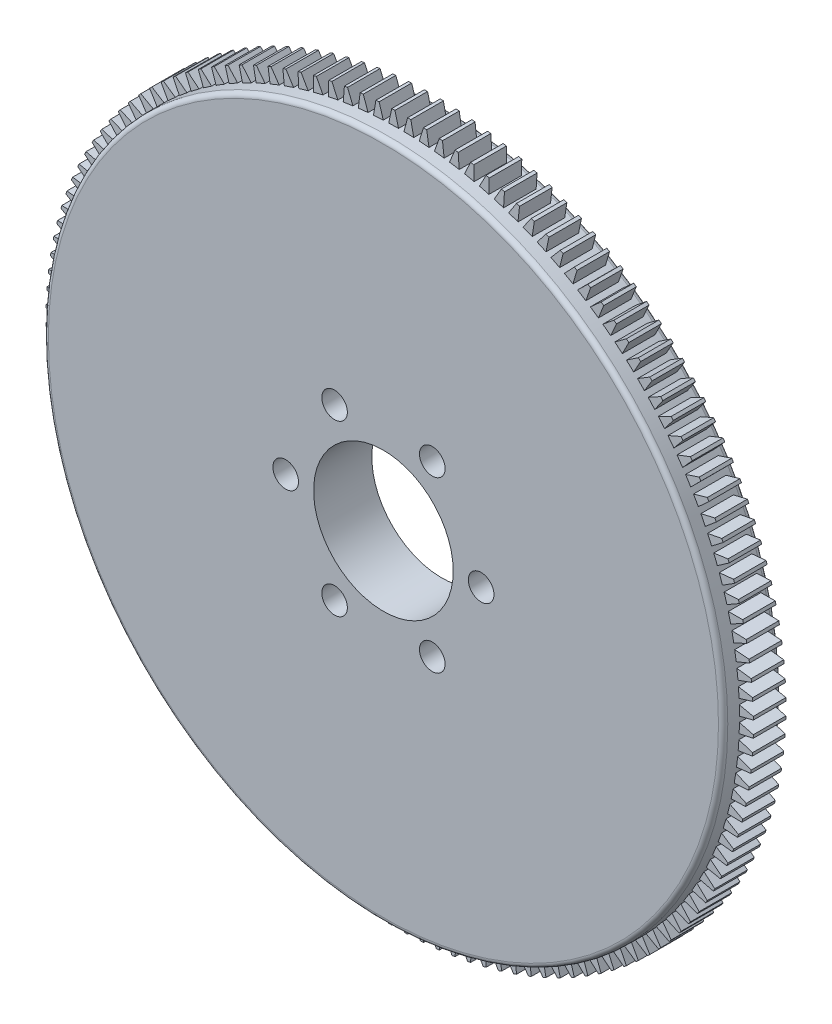
SolidWorks part; units mm, degrees
ref_plane "Front Plane" through (0, 0, 0) normal (0, 0, 1) x (1, 0, 0)
ref_plane "Top Plane" through (0, 0, 0) normal (0, 1, 0) x (1, 0, 0)
ref_plane "Right Plane" through (0, 0, 0) normal (1, 0, 0) x (0, 0, -1)
other "Configuration Table"
sketch "Sketch1" plane through (0, 0, 0) normal (1, 0, 0) x (0, 0, -1)
  line L0 (400, 0) -> (410, 0) construction
  line L1 (419, 30) -> (419, 144)
  line L2 (421, 146) -> (442, 146)
  line L3 (444, 144) -> (444, 30)
  line L4 (444, 30) -> (419, 30)
  arc A0 (419, 144) -> (421, 146) centre (421, 144) cw
  arc A1 (442, 146) -> (444, 144) centre (442, 144) cw
revolve "Plate" add sketch "Sketch1" angle 360 about L0
sketch "Sketch2" plane through (0, 0, 0) normal (1, 0, 0) x (0, 0, -1)
  line L0 (400, 0) -> (410, 0) construction
  line L1 (441.5, 80) -> (441.5, 136)
  line L2 (441.5, 136) -> (446, 136)
  line L3 (446, 136) -> (446, 80)
  line L4 (446, 80) -> (441.5, 80)
revolve "Clutch Face" cut sketch "Sketch2" angle 360 about L0
sketch "Sketch3" plane through (0, 0, 0) normal (0, 0, 1) x (1, 0, 0)
  line L0 (144, 0) -> (151.9862, 2.0465)
  line L1 (151.9862, 2.0465) -> (151.9617, 3.4106)
  line L2 (151.9617, 3.4106) -> (143.9072, 5.1691)
  line L3 (143.9072, 5.1691) -> (143.855, 6.4605)
  line L4 (143.855, 6.4605) -> (151.7414, 8.8632)
  line L5 (151.7414, 8.8632) -> (151.6557, 10.2249)
  line L6 (151.6557, 10.2249) -> (143.5304, 11.6202)
  line L7 (143.5304, 11.6202) -> (143.4203, 12.9081)
  line L8 (143.4203, 12.9081) -> (151.1909, 15.6622)
  line L9 (151.1909, 15.6622) -> (151.0443, 17.0186)
  line L10 (151.0443, 17.0186) -> (142.8645, 18.048)
  line L11 (142.8645, 18.048) -> (142.6968, 19.3296)
  line L12 (142.6968, 19.3296) -> (150.336, 22.4295)
  line L13 (150.336, 22.4295) -> (150.1286, 23.778)
  line L14 (150.1286, 23.778) -> (141.9109, 24.4394)
  line L15 (141.9109, 24.4394) -> (141.6859, 25.7122)
  line L16 (141.6859, 25.7122) -> (149.1783, 29.1518)
  line L17 (149.1783, 29.1518) -> (148.9107, 30.4896)
  line L18 (148.9107, 30.4896) -> (140.6716, 30.7816)
  line L19 (140.6716, 30.7816) -> (140.3896, 32.043)
  line L20 (140.3896, 32.043) -> (147.7202, 35.8153)
  line L21 (147.7202, 35.8153) -> (147.3928, 37.1397)
  line L22 (147.3928, 37.1397) -> (139.1489, 37.0618)
  line L23 (139.1489, 37.0618) -> (138.8107, 38.3093)
  line L24 (138.8107, 38.3093) -> (145.9646, 42.4066)
  line L25 (145.9646, 42.4066) -> (145.5781, 43.7151)
  line L26 (145.5781, 43.7151) -> (137.346, 43.2674)
  line L27 (137.346, 43.2674) -> (136.9521, 44.4984)
  line L28 (136.9521, 44.4984) -> (143.9151, 48.9126)
  line L29 (143.9151, 48.9126) -> (143.4703, 50.2024)
  line L30 (143.4703, 50.2024) -> (135.2666, 49.3858)
  line L31 (135.2666, 49.3858) -> (134.8178, 50.598)
  line L32 (134.8178, 50.598) -> (141.5757, 55.3201)
  line L33 (141.5757, 55.3201) -> (141.0735, 56.5886)
  line L34 (141.0735, 56.5886) -> (132.9147, 55.4048)
  line L35 (132.9147, 55.4048) -> (132.412, 56.5956)
  line L36 (132.412, 56.5956) -> (138.9512, 61.6162)
  line L37 (138.9512, 61.6162) -> (138.3926, 62.8609)
  line L38 (138.3926, 62.8609) -> (130.2951, 61.3122)
  line L39 (130.2951, 61.3122) -> (129.7395, 62.4793)
  line L40 (129.7395, 62.4793) -> (136.0469, 67.7881)
  line L41 (136.0469, 67.7881) -> (135.433, 69.0066)
  line L42 (135.433, 69.0066) -> (127.4131, 67.0961)
  line L43 (127.4131, 67.0961) -> (126.8058, 68.2371)
  line L44 (126.8058, 68.2371) -> (132.8686, 73.8236)
  line L45 (132.8686, 73.8236) -> (132.2007, 75.0132)
  line L46 (132.2007, 75.0132) -> (124.2746, 72.745)
  line L47 (124.2746, 72.745) -> (123.6166, 73.8575)
  line L48 (123.6166, 73.8575) -> (129.4228, 79.7104)
  line L49 (129.4228, 79.7104) -> (128.7021, 80.8689)
  line L50 (128.7021, 80.8689) -> (120.8858, 78.2473)
  line L51 (120.8858, 78.2473) -> (120.1785, 79.3292)
  line L52 (120.1785, 79.3292) -> (125.7162, 85.4367)
  line L53 (125.7162, 85.4367) -> (124.9443, 86.5616)
  line L54 (124.9443, 86.5616) -> (117.2535, 83.592)
  line L55 (117.2535, 83.592) -> (116.4984, 84.6411)
  line L56 (116.4984, 84.6411) -> (121.7566, 90.9909)
  line L57 (121.7566, 90.9909) -> (120.9349, 92.0801)
  line L58 (120.9349, 92.0801) -> (113.3851, 88.7684)
  line L59 (113.3851, 88.7684) -> (112.5837, 89.7825)
  line L60 (112.5837, 89.7825) -> (117.5517, 96.3618)
  line L61 (117.5517, 96.3618) -> (116.682, 97.4131)
  line L62 (116.682, 97.4131) -> (109.2883, 93.766)
  line L63 (109.2883, 93.766) -> (108.4423, 94.7432)
  line L64 (108.4423, 94.7432) -> (113.11, 101.5388)
  line L65 (113.11, 101.5388) -> (112.1941, 102.5499)
  line L66 (112.1941, 102.5499) -> (104.9715, 98.5748)
  line L67 (104.9715, 98.5748) -> (104.0825, 99.513)
  line L68 (104.0825, 99.513) -> (108.4406, 106.5112)
  line L69 (108.4406, 106.5112) -> (107.4802, 107.4802)
  line L70 (107.4802, 107.4802) -> (100.4432, 103.1851)
  line L71 (100.4432, 103.1851) -> (99.513, 104.0825)
  line L72 (99.513, 104.0825) -> (103.5528, 111.2691)
  line L73 (103.5528, 111.2691) -> (102.5499, 112.1941)
  line L74 (102.5499, 112.1941) -> (95.7127, 107.5875)
  line L75 (95.7127, 107.5875) -> (94.7432, 108.4423)
  line L76 (94.7432, 108.4423) -> (98.4565, 115.8029)
  line L77 (98.4565, 115.8029) -> (97.4131, 116.682)
  line L78 (97.4131, 116.682) -> (90.7895, 111.7733)
  line L79 (90.7895, 111.7733) -> (89.7825, 112.5837)
  line L80 (89.7825, 112.5837) -> (93.1619, 120.1036)
  line L81 (93.1619, 120.1036) -> (92.0801, 120.9349)
  line L82 (92.0801, 120.9349) -> (85.6833, 115.734)
  line L83 (85.6833, 115.734) -> (84.6411, 116.4984)
  line L84 (84.6411, 116.4984) -> (87.6796, 124.1623)
  line L85 (87.6796, 124.1623) -> (86.5616, 124.9443)
  line L86 (86.5616, 124.9443) -> (80.4047, 119.4617)
  line L87 (80.4047, 119.4617) -> (79.3292, 120.1785)
  line L88 (79.3292, 120.1785) -> (82.0208, 127.971)
  line L89 (82.0208, 127.971) -> (80.8689, 128.7021)
  line L90 (80.8689, 128.7021) -> (74.9641, 122.9487)
  line L91 (74.9641, 122.9487) -> (73.8575, 123.6166)
  line L92 (73.8575, 123.6166) -> (76.1968, 131.522)
  line L93 (76.1968, 131.522) -> (75.0132, 132.2007)
  line L94 (75.0132, 132.2007) -> (69.3725, 126.1882)
  line L95 (69.3725, 126.1882) -> (68.2371, 126.8058)
  line L96 (68.2371, 126.8058) -> (70.2194, 134.8081)
  line L97 (70.2194, 134.8081) -> (69.0066, 135.433)
  line L98 (69.0066, 135.433) -> (63.6413, 129.1735)
  line L99 (63.6413, 129.1735) -> (62.4793, 129.7395)
  line L100 (62.4793, 129.7395) -> (64.1006, 137.8228)
  line L101 (64.1006, 137.8228) -> (62.8609, 138.3926)
  line L102 (62.8609, 138.3926) -> (57.7818, 131.8987)
  line L103 (57.7818, 131.8987) -> (56.5956, 132.412)
  line L104 (56.5956, 132.412) -> (57.8526, 140.5599)
  line L105 (57.8526, 140.5599) -> (56.5886, 141.0735)
  line L106 (56.5886, 141.0735) -> (51.806, 134.3582)
  line L107 (51.806, 134.3582) -> (50.598, 134.8178)
  line L108 (50.598, 134.8178) -> (51.4882, 143.0139)
  line L109 (51.4882, 143.0139) -> (50.2024, 143.4703)
  line L110 (50.2024, 143.4703) -> (45.7259, 136.5472)
  line L111 (45.7259, 136.5472) -> (44.4984, 136.9521)
  line L112 (44.4984, 136.9521) -> (45.02, 145.1799)
  line L113 (45.02, 145.1799) -> (43.7151, 145.5781)
  line L114 (43.7151, 145.5781) -> (39.5537, 138.4612)
  line L115 (39.5537, 138.4612) -> (38.3093, 138.8107)
  line L116 (38.3093, 138.8107) -> (38.4612, 147.0535)
  line L117 (38.4612, 147.0535) -> (37.1397, 147.3928)
  line L118 (37.1397, 147.3928) -> (33.3018, 140.0964)
  line L119 (33.3018, 140.0964) -> (32.043, 140.3896)
  line L120 (32.043, 140.3896) -> (31.825, 148.631)
  line L121 (31.825, 148.631) -> (30.4896, 148.9107)
  line L122 (30.4896, 148.9107) -> (26.9829, 141.4494)
  line L123 (26.9829, 141.4494) -> (25.7122, 141.6859)
  line L124 (25.7122, 141.6859) -> (25.1246, 149.9092)
  line L125 (25.1246, 149.9092) -> (23.778, 150.1286)
  line L126 (23.778, 150.1286) -> (20.6096, 142.5175)
  line L127 (20.6096, 142.5175) -> (19.3296, 142.6968)
  line L128 (19.3296, 142.6968) -> (18.3737, 150.8854)
  line L129 (18.3737, 150.8854) -> (17.0186, 151.0443)
  line L130 (17.0186, 151.0443) -> (14.1949, 143.2987)
  line L131 (14.1949, 143.2987) -> (12.9081, 143.4203)
  line L132 (12.9081, 143.4203) -> (11.5857, 151.5578)
  line L133 (11.5857, 151.5578) -> (10.2249, 151.6557)
  line L134 (10.2249, 151.6557) -> (7.7515, 143.7912)
  line L135 (7.7515, 143.7912) -> (6.4605, 143.855)
  line L136 (6.4605, 143.855) -> (4.7744, 151.925)
  line L137 (4.7744, 151.925) -> (3.4106, 151.9617)
  line L138 (3.4106, 151.9617) -> (1.2925, 143.9942)
  line L139 (1.2925, 143.9942) -> (0, 144)
  line L140 (0, 144) -> (-2.0465, 151.9862)
  line L141 (-2.0465, 151.9862) -> (-3.4106, 151.9617)
  line L142 (-3.4106, 151.9617) -> (-5.1691, 143.9072)
  line L143 (-5.1691, 143.9072) -> (-6.4605, 143.855)
  line L144 (-6.4605, 143.855) -> (-8.8632, 151.7414)
  line L145 (-8.8632, 151.7414) -> (-10.2249, 151.6557)
  line L146 (-10.2249, 151.6557) -> (-11.6202, 143.5304)
  line L147 (-11.6202, 143.5304) -> (-12.9081, 143.4203)
  line L148 (-12.9081, 143.4203) -> (-15.6622, 151.1909)
  line L149 (-15.6622, 151.1909) -> (-17.0186, 151.0443)
  line L150 (-17.0186, 151.0443) -> (-18.048, 142.8645)
  line L151 (-18.048, 142.8645) -> (-19.3296, 142.6968)
  line L152 (-19.3296, 142.6968) -> (-22.4295, 150.336)
  line L153 (-22.4295, 150.336) -> (-23.778, 150.1286)
  line L154 (-23.778, 150.1286) -> (-24.4394, 141.9109)
  line L155 (-24.4394, 141.9109) -> (-25.7122, 141.6859)
  line L156 (-25.7122, 141.6859) -> (-29.1518, 149.1783)
  line L157 (-29.1518, 149.1783) -> (-30.4896, 148.9107)
  line L158 (-30.4896, 148.9107) -> (-30.7816, 140.6716)
  line L159 (-30.7816, 140.6716) -> (-32.043, 140.3896)
  line L160 (-32.043, 140.3896) -> (-35.8153, 147.7202)
  line L161 (-35.8153, 147.7202) -> (-37.1397, 147.3928)
  line L162 (-37.1397, 147.3928) -> (-37.0618, 139.1489)
  line L163 (-37.0618, 139.1489) -> (-38.3093, 138.8107)
  line L164 (-38.3093, 138.8107) -> (-42.4066, 145.9646)
  line L165 (-42.4066, 145.9646) -> (-43.7151, 145.5781)
  line L166 (-43.7151, 145.5781) -> (-43.2674, 137.346)
  line L167 (-43.2674, 137.346) -> (-44.4984, 136.9521)
  line L168 (-44.4984, 136.9521) -> (-48.9126, 143.9151)
  line L169 (-48.9126, 143.9151) -> (-50.2024, 143.4703)
  line L170 (-50.2024, 143.4703) -> (-49.3858, 135.2666)
  line L171 (-49.3858, 135.2666) -> (-50.598, 134.8178)
  line L172 (-50.598, 134.8178) -> (-55.3201, 141.5757)
  line L173 (-55.3201, 141.5757) -> (-56.5886, 141.0735)
  line L174 (-56.5886, 141.0735) -> (-55.4048, 132.9147)
  line L175 (-55.4048, 132.9147) -> (-56.5956, 132.412)
  line L176 (-56.5956, 132.412) -> (-61.6162, 138.9512)
  line L177 (-61.6162, 138.9512) -> (-62.8609, 138.3926)
  line L178 (-62.8609, 138.3926) -> (-61.3122, 130.2951)
  line L179 (-61.3122, 130.2951) -> (-62.4793, 129.7395)
  line L180 (-62.4793, 129.7395) -> (-67.7881, 136.0469)
  line L181 (-67.7881, 136.0469) -> (-69.0066, 135.433)
  line L182 (-69.0066, 135.433) -> (-67.0961, 127.4131)
  line L183 (-67.0961, 127.4131) -> (-68.2371, 126.8058)
  line L184 (-68.2371, 126.8058) -> (-73.8236, 132.8686)
  line L185 (-73.8236, 132.8686) -> (-75.0132, 132.2007)
  line L186 (-75.0132, 132.2007) -> (-72.745, 124.2746)
  line L187 (-72.745, 124.2746) -> (-73.8575, 123.6166)
  line L188 (-73.8575, 123.6166) -> (-79.7104, 129.4228)
  line L189 (-79.7104, 129.4228) -> (-80.8689, 128.7021)
  line L190 (-80.8689, 128.7021) -> (-78.2473, 120.8858)
  line L191 (-78.2473, 120.8858) -> (-79.3292, 120.1785)
  line L192 (-79.3292, 120.1785) -> (-85.4367, 125.7162)
  line L193 (-85.4367, 125.7162) -> (-86.5616, 124.9443)
  line L194 (-86.5616, 124.9443) -> (-83.592, 117.2535)
  line L195 (-83.592, 117.2535) -> (-84.6411, 116.4984)
  line L196 (-84.6411, 116.4984) -> (-90.9909, 121.7566)
  line L197 (-90.9909, 121.7566) -> (-92.0801, 120.9349)
  line L198 (-92.0801, 120.9349) -> (-88.7684, 113.3851)
  line L199 (-88.7684, 113.3851) -> (-89.7825, 112.5837)
  line L200 (-89.7825, 112.5837) -> (-96.3618, 117.5517)
  line L201 (-96.3618, 117.5517) -> (-97.4131, 116.682)
  line L202 (-97.4131, 116.682) -> (-93.766, 109.2883)
  line L203 (-93.766, 109.2883) -> (-94.7432, 108.4423)
  line L204 (-94.7432, 108.4423) -> (-101.5388, 113.11)
  line L205 (-101.5388, 113.11) -> (-102.5499, 112.1941)
  line L206 (-102.5499, 112.1941) -> (-98.5748, 104.9715)
  line L207 (-98.5748, 104.9715) -> (-99.513, 104.0825)
  line L208 (-99.513, 104.0825) -> (-106.5112, 108.4406)
  line L209 (-106.5112, 108.4406) -> (-107.4802, 107.4802)
  line L210 (-107.4802, 107.4802) -> (-103.1851, 100.4432)
  line L211 (-103.1851, 100.4432) -> (-104.0825, 99.513)
  line L212 (-104.0825, 99.513) -> (-111.2691, 103.5528)
  line L213 (-111.2691, 103.5528) -> (-112.1941, 102.5499)
  line L214 (-112.1941, 102.5499) -> (-107.5875, 95.7127)
  line L215 (-107.5875, 95.7127) -> (-108.4423, 94.7432)
  line L216 (-108.4423, 94.7432) -> (-115.8029, 98.4565)
  line L217 (-115.8029, 98.4565) -> (-116.682, 97.4131)
  line L218 (-116.682, 97.4131) -> (-111.7733, 90.7895)
  line L219 (-111.7733, 90.7895) -> (-112.5837, 89.7825)
  line L220 (-112.5837, 89.7825) -> (-120.1036, 93.1619)
  line L221 (-120.1036, 93.1619) -> (-120.9349, 92.0801)
  line L222 (-120.9349, 92.0801) -> (-115.734, 85.6833)
  line L223 (-115.734, 85.6833) -> (-116.4984, 84.6411)
  line L224 (-116.4984, 84.6411) -> (-124.1623, 87.6796)
  line L225 (-124.1623, 87.6796) -> (-124.9443, 86.5616)
  line L226 (-124.9443, 86.5616) -> (-119.4617, 80.4047)
  line L227 (-119.4617, 80.4047) -> (-120.1785, 79.3292)
  line L228 (-120.1785, 79.3292) -> (-127.971, 82.0208)
  line L229 (-127.971, 82.0208) -> (-128.7021, 80.8689)
  line L230 (-128.7021, 80.8689) -> (-122.9487, 74.9641)
  line L231 (-122.9487, 74.9641) -> (-123.6166, 73.8575)
  line L232 (-123.6166, 73.8575) -> (-131.522, 76.1968)
  line L233 (-131.522, 76.1968) -> (-132.2007, 75.0132)
  line L234 (-132.2007, 75.0132) -> (-126.1882, 69.3725)
  line L235 (-126.1882, 69.3725) -> (-126.8058, 68.2371)
  line L236 (-126.8058, 68.2371) -> (-134.8081, 70.2194)
  line L237 (-134.8081, 70.2194) -> (-135.433, 69.0066)
  line L238 (-135.433, 69.0066) -> (-129.1735, 63.6413)
  line L239 (-129.1735, 63.6413) -> (-129.7395, 62.4793)
  line L240 (-129.7395, 62.4793) -> (-137.8228, 64.1006)
  line L241 (-137.8228, 64.1006) -> (-138.3926, 62.8609)
  line L242 (-138.3926, 62.8609) -> (-131.8987, 57.7818)
  line L243 (-131.8987, 57.7818) -> (-132.412, 56.5956)
  line L244 (-132.412, 56.5956) -> (-140.5599, 57.8526)
  line L245 (-140.5599, 57.8526) -> (-141.0735, 56.5886)
  line L246 (-141.0735, 56.5886) -> (-134.3582, 51.806)
  line L247 (-134.3582, 51.806) -> (-134.8178, 50.598)
  line L248 (-134.8178, 50.598) -> (-143.0139, 51.4882)
  line L249 (-143.0139, 51.4882) -> (-143.4703, 50.2024)
  line L250 (-143.4703, 50.2024) -> (-136.5472, 45.7259)
  line L251 (-136.5472, 45.7259) -> (-136.9521, 44.4984)
  line L252 (-136.9521, 44.4984) -> (-145.1799, 45.02)
  line L253 (-145.1799, 45.02) -> (-145.5781, 43.7151)
  line L254 (-145.5781, 43.7151) -> (-138.4612, 39.5537)
  line L255 (-138.4612, 39.5537) -> (-138.8107, 38.3093)
  line L256 (-138.8107, 38.3093) -> (-147.0535, 38.4612)
  line L257 (-147.0535, 38.4612) -> (-147.3928, 37.1397)
  line L258 (-147.3928, 37.1397) -> (-140.0964, 33.3018)
  line L259 (-140.0964, 33.3018) -> (-140.3896, 32.043)
  line L260 (-140.3896, 32.043) -> (-148.631, 31.825)
  line L261 (-148.631, 31.825) -> (-148.9107, 30.4896)
  line L262 (-148.9107, 30.4896) -> (-141.4494, 26.9829)
  line L263 (-141.4494, 26.9829) -> (-141.6859, 25.7122)
  line L264 (-141.6859, 25.7122) -> (-149.9092, 25.1246)
  line L265 (-149.9092, 25.1246) -> (-150.1286, 23.778)
  line L266 (-150.1286, 23.778) -> (-142.5175, 20.6096)
  line L267 (-142.5175, 20.6096) -> (-142.6968, 19.3296)
  line L268 (-142.6968, 19.3296) -> (-150.8854, 18.3737)
  line L269 (-150.8854, 18.3737) -> (-151.0443, 17.0186)
  line L270 (-151.0443, 17.0186) -> (-143.2987, 14.1949)
  line L271 (-143.2987, 14.1949) -> (-143.4203, 12.9081)
  line L272 (-143.4203, 12.9081) -> (-151.5578, 11.5857)
  line L273 (-151.5578, 11.5857) -> (-151.6557, 10.2249)
  line L274 (-151.6557, 10.2249) -> (-143.7912, 7.7515)
  line L275 (-143.7912, 7.7515) -> (-143.855, 6.4605)
  line L276 (-143.855, 6.4605) -> (-151.925, 4.7744)
  line L277 (-151.925, 4.7744) -> (-151.9617, 3.4106)
  line L278 (-151.9617, 3.4106) -> (-143.9942, 1.2925)
  line L279 (-143.9942, 1.2925) -> (-144, 0)
  line L280 (-144, 0) -> (-151.9862, -2.0465)
  line L281 (-151.9862, -2.0465) -> (-151.9617, -3.4106)
  line L282 (-151.9617, -3.4106) -> (-143.9072, -5.1691)
  line L283 (-143.9072, -5.1691) -> (-143.855, -6.4605)
  line L284 (-143.855, -6.4605) -> (-151.7414, -8.8632)
  line L285 (-151.7414, -8.8632) -> (-151.6557, -10.2249)
  line L286 (-151.6557, -10.2249) -> (-143.5304, -11.6202)
  line L287 (-143.5304, -11.6202) -> (-143.4203, -12.9081)
  line L288 (-143.4203, -12.9081) -> (-151.1909, -15.6622)
  line L289 (-151.1909, -15.6622) -> (-151.0443, -17.0186)
  line L290 (-151.0443, -17.0186) -> (-142.8645, -18.048)
  line L291 (-142.8645, -18.048) -> (-142.6968, -19.3296)
  line L292 (-142.6968, -19.3296) -> (-150.336, -22.4295)
  line L293 (-150.336, -22.4295) -> (-150.1286, -23.778)
  line L294 (-150.1286, -23.778) -> (-141.9109, -24.4394)
  line L295 (-141.9109, -24.4394) -> (-141.6859, -25.7122)
  line L296 (-141.6859, -25.7122) -> (-149.1783, -29.1518)
  line L297 (-149.1783, -29.1518) -> (-148.9107, -30.4896)
  line L298 (-148.9107, -30.4896) -> (-140.6716, -30.7816)
  line L299 (-140.6716, -30.7816) -> (-140.3896, -32.043)
  line L300 (-140.3896, -32.043) -> (-147.7202, -35.8153)
  line L301 (-147.7202, -35.8153) -> (-147.3928, -37.1397)
  line L302 (-147.3928, -37.1397) -> (-139.1489, -37.0618)
  line L303 (-139.1489, -37.0618) -> (-138.8107, -38.3093)
  line L304 (-138.8107, -38.3093) -> (-145.9646, -42.4066)
  line L305 (-145.9646, -42.4066) -> (-145.5781, -43.7151)
  line L306 (-145.5781, -43.7151) -> (-137.346, -43.2674)
  line L307 (-137.346, -43.2674) -> (-136.9521, -44.4984)
  line L308 (-136.9521, -44.4984) -> (-143.9151, -48.9126)
  line L309 (-143.9151, -48.9126) -> (-143.4703, -50.2024)
  line L310 (-143.4703, -50.2024) -> (-135.2666, -49.3858)
  line L311 (-135.2666, -49.3858) -> (-134.8178, -50.598)
  line L312 (-134.8178, -50.598) -> (-141.5757, -55.3201)
  line L313 (-141.5757, -55.3201) -> (-141.0735, -56.5886)
  line L314 (-141.0735, -56.5886) -> (-132.9147, -55.4048)
  line L315 (-132.9147, -55.4048) -> (-132.412, -56.5956)
  line L316 (-132.412, -56.5956) -> (-138.9512, -61.6162)
  line L317 (-138.9512, -61.6162) -> (-138.3926, -62.8609)
  line L318 (-138.3926, -62.8609) -> (-130.2951, -61.3122)
  line L319 (-130.2951, -61.3122) -> (-129.7395, -62.4793)
  line L320 (-129.7395, -62.4793) -> (-136.0469, -67.7881)
  line L321 (-136.0469, -67.7881) -> (-135.433, -69.0066)
  line L322 (-135.433, -69.0066) -> (-127.4131, -67.0961)
  line L323 (-127.4131, -67.0961) -> (-126.8058, -68.2371)
  line L324 (-126.8058, -68.2371) -> (-132.8686, -73.8236)
  line L325 (-132.8686, -73.8236) -> (-132.2007, -75.0132)
  line L326 (-132.2007, -75.0132) -> (-124.2746, -72.745)
  line L327 (-124.2746, -72.745) -> (-123.6166, -73.8575)
  line L328 (-123.6166, -73.8575) -> (-129.4228, -79.7104)
  line L329 (-129.4228, -79.7104) -> (-128.7021, -80.8689)
  line L330 (-128.7021, -80.8689) -> (-120.8858, -78.2473)
  line L331 (-120.8858, -78.2473) -> (-120.1785, -79.3292)
  line L332 (-120.1785, -79.3292) -> (-125.7162, -85.4367)
  line L333 (-125.7162, -85.4367) -> (-124.9443, -86.5616)
  line L334 (-124.9443, -86.5616) -> (-117.2535, -83.592)
  line L335 (-117.2535, -83.592) -> (-116.4984, -84.6411)
  line L336 (-116.4984, -84.6411) -> (-121.7566, -90.9909)
  line L337 (-121.7566, -90.9909) -> (-120.9349, -92.0801)
  line L338 (-120.9349, -92.0801) -> (-113.3851, -88.7684)
  line L339 (-113.3851, -88.7684) -> (-112.5837, -89.7825)
  line L340 (-112.5837, -89.7825) -> (-117.5517, -96.3618)
  line L341 (-117.5517, -96.3618) -> (-116.682, -97.4131)
  line L342 (-116.682, -97.4131) -> (-109.2883, -93.766)
  line L343 (-109.2883, -93.766) -> (-108.4423, -94.7432)
  line L344 (-108.4423, -94.7432) -> (-113.11, -101.5388)
  line L345 (-113.11, -101.5388) -> (-112.1941, -102.5499)
  line L346 (-112.1941, -102.5499) -> (-104.9715, -98.5748)
  line L347 (-104.9715, -98.5748) -> (-104.0825, -99.513)
  line L348 (-104.0825, -99.513) -> (-108.4406, -106.5112)
  line L349 (-108.4406, -106.5112) -> (-107.4802, -107.4802)
  line L350 (-107.4802, -107.4802) -> (-100.4432, -103.1851)
  line L351 (-100.4432, -103.1851) -> (-99.513, -104.0825)
  line L352 (-99.513, -104.0825) -> (-103.5528, -111.2691)
  line L353 (-103.5528, -111.2691) -> (-102.5499, -112.1941)
  line L354 (-102.5499, -112.1941) -> (-95.7127, -107.5875)
  line L355 (-95.7127, -107.5875) -> (-94.7432, -108.4423)
  line L356 (-94.7432, -108.4423) -> (-98.4565, -115.8029)
  line L357 (-98.4565, -115.8029) -> (-97.4131, -116.682)
  line L358 (-97.4131, -116.682) -> (-90.7895, -111.7733)
  line L359 (-90.7895, -111.7733) -> (-89.7825, -112.5837)
  line L360 (-89.7825, -112.5837) -> (-93.1619, -120.1036)
  line L361 (-93.1619, -120.1036) -> (-92.0801, -120.9349)
  line L362 (-92.0801, -120.9349) -> (-85.6833, -115.734)
  line L363 (-85.6833, -115.734) -> (-84.6411, -116.4984)
  line L364 (-84.6411, -116.4984) -> (-87.6796, -124.1623)
  line L365 (-87.6796, -124.1623) -> (-86.5616, -124.9443)
  line L366 (-86.5616, -124.9443) -> (-80.4047, -119.4617)
  line L367 (-80.4047, -119.4617) -> (-79.3292, -120.1785)
  line L368 (-79.3292, -120.1785) -> (-82.0208, -127.971)
  line L369 (-82.0208, -127.971) -> (-80.8689, -128.7021)
  line L370 (-80.8689, -128.7021) -> (-74.9641, -122.9487)
  line L371 (-74.9641, -122.9487) -> (-73.8575, -123.6166)
  line L372 (-73.8575, -123.6166) -> (-76.1968, -131.522)
  line L373 (-76.1968, -131.522) -> (-75.0132, -132.2007)
  line L374 (-75.0132, -132.2007) -> (-69.3725, -126.1882)
  line L375 (-69.3725, -126.1882) -> (-68.2371, -126.8058)
  line L376 (-68.2371, -126.8058) -> (-70.2194, -134.8081)
  line L377 (-70.2194, -134.8081) -> (-69.0066, -135.433)
  line L378 (-69.0066, -135.433) -> (-63.6413, -129.1735)
  line L379 (-63.6413, -129.1735) -> (-62.4793, -129.7395)
  line L380 (-62.4793, -129.7395) -> (-64.1006, -137.8228)
  line L381 (-64.1006, -137.8228) -> (-62.8609, -138.3926)
  line L382 (-62.8609, -138.3926) -> (-57.7818, -131.8987)
  line L383 (-57.7818, -131.8987) -> (-56.5956, -132.412)
  line L384 (-56.5956, -132.412) -> (-57.8526, -140.5599)
  line L385 (-57.8526, -140.5599) -> (-56.5886, -141.0735)
  line L386 (-56.5886, -141.0735) -> (-51.806, -134.3582)
  line L387 (-51.806, -134.3582) -> (-50.598, -134.8178)
  line L388 (-50.598, -134.8178) -> (-51.4882, -143.0139)
  line L389 (-51.4882, -143.0139) -> (-50.2024, -143.4703)
  line L390 (-50.2024, -143.4703) -> (-45.7259, -136.5472)
  line L391 (-45.7259, -136.5472) -> (-44.4984, -136.9521)
  line L392 (-44.4984, -136.9521) -> (-45.02, -145.1799)
  line L393 (-45.02, -145.1799) -> (-43.7151, -145.5781)
  line L394 (-43.7151, -145.5781) -> (-39.5537, -138.4612)
  line L395 (-39.5537, -138.4612) -> (-38.3093, -138.8107)
  line L396 (-38.3093, -138.8107) -> (-38.4612, -147.0535)
  line L397 (-38.4612, -147.0535) -> (-37.1397, -147.3928)
  line L398 (-37.1397, -147.3928) -> (-33.3018, -140.0964)
  line L399 (-33.3018, -140.0964) -> (-32.043, -140.3896)
  line L400 (-32.043, -140.3896) -> (-31.825, -148.631)
  line L401 (-31.825, -148.631) -> (-30.4896, -148.9107)
  line L402 (-30.4896, -148.9107) -> (-26.9829, -141.4494)
  line L403 (-26.9829, -141.4494) -> (-25.7122, -141.6859)
  line L404 (-25.7122, -141.6859) -> (-25.1246, -149.9092)
  line L405 (-25.1246, -149.9092) -> (-23.778, -150.1286)
  line L406 (-23.778, -150.1286) -> (-20.6096, -142.5175)
  line L407 (-20.6096, -142.5175) -> (-19.3296, -142.6968)
  line L408 (-19.3296, -142.6968) -> (-18.3737, -150.8854)
  line L409 (-18.3737, -150.8854) -> (-17.0186, -151.0443)
  line L410 (-17.0186, -151.0443) -> (-14.1949, -143.2987)
  line L411 (-14.1949, -143.2987) -> (-12.9081, -143.4203)
  line L412 (-12.9081, -143.4203) -> (-11.5857, -151.5578)
  line L413 (-11.5857, -151.5578) -> (-10.2249, -151.6557)
  line L414 (-10.2249, -151.6557) -> (-7.7515, -143.7912)
  line L415 (-7.7515, -143.7912) -> (-6.4605, -143.855)
  line L416 (-6.4605, -143.855) -> (-4.7744, -151.925)
  line L417 (-4.7744, -151.925) -> (-3.4106, -151.9617)
  line L418 (-3.4106, -151.9617) -> (-1.2925, -143.9942)
  line L419 (-1.2925, -143.9942) -> (0, -144)
  line L420 (0, -144) -> (2.0465, -151.9862)
  line L421 (2.0465, -151.9862) -> (3.4106, -151.9617)
  line L422 (3.4106, -151.9617) -> (5.1691, -143.9072)
  line L423 (5.1691, -143.9072) -> (6.4605, -143.855)
  line L424 (6.4605, -143.855) -> (8.8632, -151.7414)
  line L425 (8.8632, -151.7414) -> (10.2249, -151.6557)
  line L426 (10.2249, -151.6557) -> (11.6202, -143.5304)
  line L427 (11.6202, -143.5304) -> (12.9081, -143.4203)
  line L428 (12.9081, -143.4203) -> (15.6622, -151.1909)
  line L429 (15.6622, -151.1909) -> (17.0186, -151.0443)
  line L430 (17.0186, -151.0443) -> (18.048, -142.8645)
  line L431 (18.048, -142.8645) -> (19.3296, -142.6968)
  line L432 (19.3296, -142.6968) -> (22.4295, -150.336)
  line L433 (22.4295, -150.336) -> (23.778, -150.1286)
  line L434 (23.778, -150.1286) -> (24.4394, -141.9109)
  line L435 (24.4394, -141.9109) -> (25.7122, -141.6859)
  line L436 (25.7122, -141.6859) -> (29.1518, -149.1783)
  line L437 (29.1518, -149.1783) -> (30.4896, -148.9107)
  line L438 (30.4896, -148.9107) -> (30.7816, -140.6716)
  line L439 (30.7816, -140.6716) -> (32.043, -140.3896)
  line L440 (32.043, -140.3896) -> (35.8153, -147.7202)
  line L441 (35.8153, -147.7202) -> (37.1397, -147.3928)
  line L442 (37.1397, -147.3928) -> (37.0618, -139.1489)
  line L443 (37.0618, -139.1489) -> (38.3093, -138.8107)
  line L444 (38.3093, -138.8107) -> (42.4066, -145.9646)
  line L445 (42.4066, -145.9646) -> (43.7151, -145.5781)
  line L446 (43.7151, -145.5781) -> (43.2674, -137.346)
  line L447 (43.2674, -137.346) -> (44.4984, -136.9521)
  line L448 (44.4984, -136.9521) -> (48.9126, -143.9151)
  line L449 (48.9126, -143.9151) -> (50.2024, -143.4703)
  line L450 (50.2024, -143.4703) -> (49.3858, -135.2666)
  line L451 (49.3858, -135.2666) -> (50.598, -134.8178)
  line L452 (50.598, -134.8178) -> (55.3201, -141.5757)
  line L453 (55.3201, -141.5757) -> (56.5886, -141.0735)
  line L454 (56.5886, -141.0735) -> (55.4048, -132.9147)
  line L455 (55.4048, -132.9147) -> (56.5956, -132.412)
  line L456 (56.5956, -132.412) -> (61.6162, -138.9512)
  line L457 (61.6162, -138.9512) -> (62.8609, -138.3926)
  line L458 (62.8609, -138.3926) -> (61.3122, -130.2951)
  line L459 (61.3122, -130.2951) -> (62.4793, -129.7395)
  line L460 (62.4793, -129.7395) -> (67.7881, -136.0469)
  line L461 (67.7881, -136.0469) -> (69.0066, -135.433)
  line L462 (69.0066, -135.433) -> (67.0961, -127.4131)
  line L463 (67.0961, -127.4131) -> (68.2371, -126.8058)
  line L464 (68.2371, -126.8058) -> (73.8236, -132.8686)
  line L465 (73.8236, -132.8686) -> (75.0132, -132.2007)
  line L466 (75.0132, -132.2007) -> (72.745, -124.2746)
  line L467 (72.745, -124.2746) -> (73.8575, -123.6166)
  line L468 (73.8575, -123.6166) -> (79.7104, -129.4228)
  line L469 (79.7104, -129.4228) -> (80.8689, -128.7021)
  line L470 (80.8689, -128.7021) -> (78.2473, -120.8858)
  line L471 (78.2473, -120.8858) -> (79.3292, -120.1785)
  line L472 (79.3292, -120.1785) -> (85.4367, -125.7162)
  line L473 (85.4367, -125.7162) -> (86.5616, -124.9443)
  line L474 (86.5616, -124.9443) -> (83.592, -117.2535)
  line L475 (83.592, -117.2535) -> (84.6411, -116.4984)
  line L476 (84.6411, -116.4984) -> (90.9909, -121.7566)
  line L477 (90.9909, -121.7566) -> (92.0801, -120.9349)
  line L478 (92.0801, -120.9349) -> (88.7684, -113.3851)
  line L479 (88.7684, -113.3851) -> (89.7825, -112.5837)
  line L480 (89.7825, -112.5837) -> (96.3618, -117.5517)
  line L481 (96.3618, -117.5517) -> (97.4131, -116.682)
  line L482 (97.4131, -116.682) -> (93.766, -109.2883)
  line L483 (93.766, -109.2883) -> (94.7432, -108.4423)
  line L484 (94.7432, -108.4423) -> (101.5388, -113.11)
  line L485 (101.5388, -113.11) -> (102.5499, -112.1941)
  line L486 (102.5499, -112.1941) -> (98.5748, -104.9715)
  line L487 (98.5748, -104.9715) -> (99.513, -104.0825)
  line L488 (99.513, -104.0825) -> (106.5112, -108.4406)
  line L489 (106.5112, -108.4406) -> (107.4802, -107.4802)
  line L490 (107.4802, -107.4802) -> (103.1851, -100.4432)
  line L491 (103.1851, -100.4432) -> (104.0825, -99.513)
  line L492 (104.0825, -99.513) -> (111.2691, -103.5528)
  line L493 (111.2691, -103.5528) -> (112.1941, -102.5499)
  line L494 (112.1941, -102.5499) -> (107.5875, -95.7127)
  line L495 (107.5875, -95.7127) -> (108.4423, -94.7432)
  line L496 (108.4423, -94.7432) -> (115.8029, -98.4565)
  line L497 (115.8029, -98.4565) -> (116.682, -97.4131)
  line L498 (116.682, -97.4131) -> (111.7733, -90.7895)
  line L499 (111.7733, -90.7895) -> (112.5837, -89.7825)
  line L500 (112.5837, -89.7825) -> (120.1036, -93.1619)
  line L501 (120.1036, -93.1619) -> (120.9349, -92.0801)
  line L502 (120.9349, -92.0801) -> (115.734, -85.6833)
  line L503 (115.734, -85.6833) -> (116.4984, -84.6411)
  line L504 (116.4984, -84.6411) -> (124.1623, -87.6796)
  line L505 (124.1623, -87.6796) -> (124.9443, -86.5616)
  line L506 (124.9443, -86.5616) -> (119.4617, -80.4047)
  line L507 (119.4617, -80.4047) -> (120.1785, -79.3292)
  line L508 (120.1785, -79.3292) -> (127.971, -82.0208)
  line L509 (127.971, -82.0208) -> (128.7021, -80.8689)
  line L510 (128.7021, -80.8689) -> (122.9487, -74.9641)
  line L511 (122.9487, -74.9641) -> (123.6166, -73.8575)
  line L512 (123.6166, -73.8575) -> (131.522, -76.1968)
  line L513 (131.522, -76.1968) -> (132.2007, -75.0132)
  line L514 (132.2007, -75.0132) -> (126.1882, -69.3725)
  line L515 (126.1882, -69.3725) -> (126.8058, -68.2371)
  line L516 (126.8058, -68.2371) -> (134.8081, -70.2194)
  line L517 (134.8081, -70.2194) -> (135.433, -69.0066)
  line L518 (135.433, -69.0066) -> (129.1735, -63.6413)
  line L519 (129.1735, -63.6413) -> (129.7395, -62.4793)
  line L520 (129.7395, -62.4793) -> (137.8228, -64.1006)
  line L521 (137.8228, -64.1006) -> (138.3926, -62.8609)
  line L522 (138.3926, -62.8609) -> (131.8987, -57.7818)
  line L523 (131.8987, -57.7818) -> (132.412, -56.5956)
  line L524 (132.412, -56.5956) -> (140.5599, -57.8526)
  line L525 (140.5599, -57.8526) -> (141.0735, -56.5886)
  line L526 (141.0735, -56.5886) -> (134.3582, -51.806)
  line L527 (134.3582, -51.806) -> (134.8178, -50.598)
  line L528 (134.8178, -50.598) -> (143.0139, -51.4882)
  line L529 (143.0139, -51.4882) -> (143.4703, -50.2024)
  line L530 (143.4703, -50.2024) -> (136.5472, -45.7259)
  line L531 (136.5472, -45.7259) -> (136.9521, -44.4984)
  line L532 (136.9521, -44.4984) -> (145.1799, -45.02)
  line L533 (145.1799, -45.02) -> (145.5781, -43.7151)
  line L534 (145.5781, -43.7151) -> (138.4612, -39.5537)
  line L535 (138.4612, -39.5537) -> (138.8107, -38.3093)
  line L536 (138.8107, -38.3093) -> (147.0535, -38.4612)
  line L537 (147.0535, -38.4612) -> (147.3928, -37.1397)
  line L538 (147.3928, -37.1397) -> (140.0964, -33.3018)
  line L539 (140.0964, -33.3018) -> (140.3896, -32.043)
  line L540 (140.3896, -32.043) -> (148.631, -31.825)
  line L541 (148.631, -31.825) -> (148.9107, -30.4896)
  line L542 (148.9107, -30.4896) -> (141.4494, -26.9829)
  line L543 (141.4494, -26.9829) -> (141.6859, -25.7122)
  line L544 (141.6859, -25.7122) -> (149.9092, -25.1246)
  line L545 (149.9092, -25.1246) -> (150.1286, -23.778)
  line L546 (150.1286, -23.778) -> (142.5175, -20.6096)
  line L547 (142.5175, -20.6096) -> (142.6968, -19.3296)
  line L548 (142.6968, -19.3296) -> (150.8854, -18.3737)
  line L549 (150.8854, -18.3737) -> (151.0443, -17.0186)
  line L550 (151.0443, -17.0186) -> (143.2987, -14.1949)
  line L551 (143.2987, -14.1949) -> (143.4203, -12.9081)
  line L552 (143.4203, -12.9081) -> (151.5578, -11.5857)
  line L553 (151.5578, -11.5857) -> (151.6557, -10.2249)
  line L554 (151.6557, -10.2249) -> (143.7912, -7.7515)
  line L555 (143.7912, -7.7515) -> (143.855, -6.4605)
  line L556 (143.855, -6.4605) -> (151.925, -4.7744)
  line L557 (151.925, -4.7744) -> (151.9617, -3.4106)
  line L558 (151.9617, -3.4106) -> (143.9942, -1.2925)
  line L559 (143.9942, -1.2925) -> (144, 0)
  circle A0 centre (0, 0) radius 120
extrude "Ring Gear" add sketch "Sketch3" along normal blind 14 from offset 440
sketch "Sketch4" plane through (0, 0, 0) normal (0, 0, 1) x (1, 0, 0)
  circle A0 centre (42, 0) radius 5.5
  circle A1 centre (21, 36.3731) radius 5.5
  circle A2 centre (-21, 36.3731) radius 5.5
  circle A3 centre (-42, 0) radius 5.5
  circle A4 centre (-21, -36.3731) radius 5.5
  circle A5 centre (21, -36.3731) radius 5.5
extrude "Crank Bolt Holes" cut sketch "Sketch4" against normal through all and the other way through all
